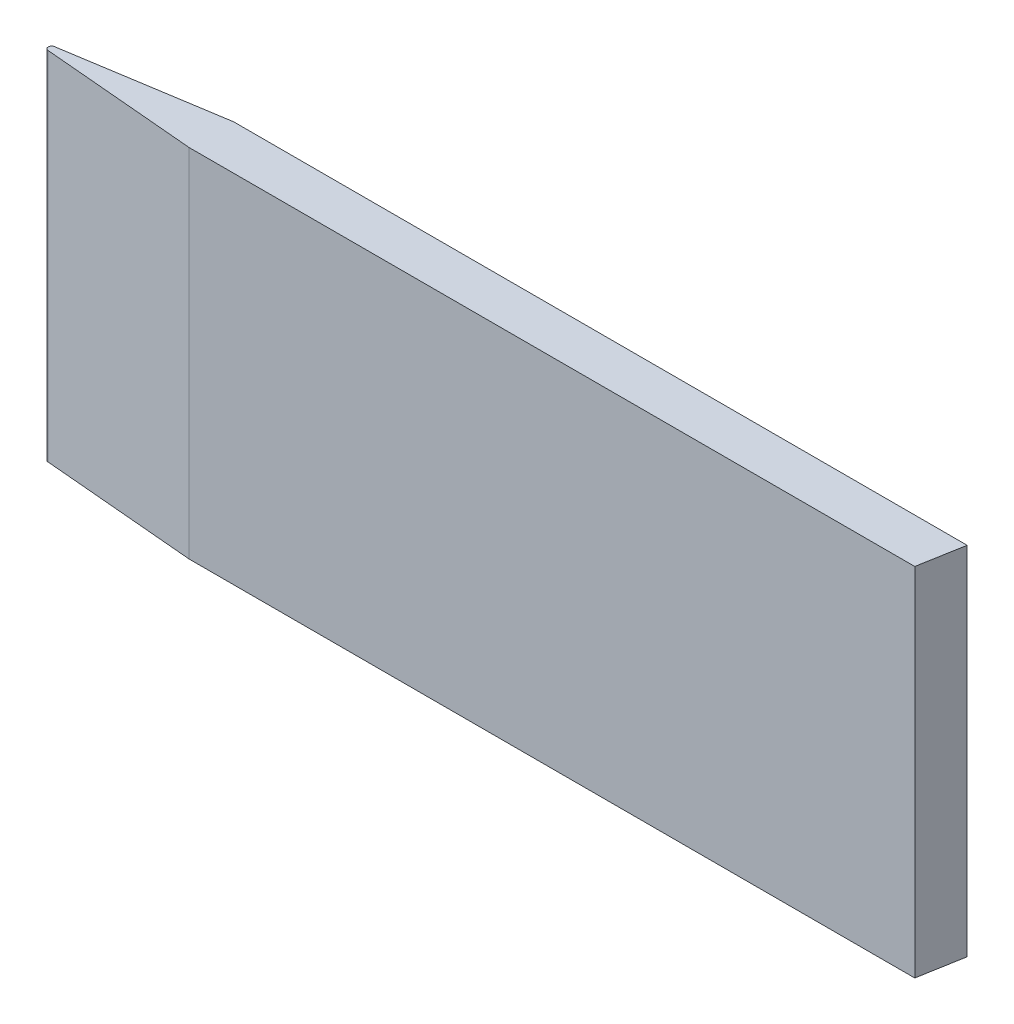
SolidWorks part; units mm, degrees
material "Acrylic (Medium-high impact)"
ref_plane "Front Plane" through (0, 0, 0) normal (0, 0, 1) x (1, 0, 0)
ref_plane "Top Plane" through (0, 0, 0) normal (0, 1, 0) x (1, 0, 0)
ref_plane "Right Plane" through (0, 0, 0) normal (1, 0, 0) x (0, 0, -1)
sketch "Sketch1" plane through (0, 0, 0) normal (0, 1, 0) x (1, 0, 0)
  line L0 (100, 5) -> (98.2367, -5)
  line L1 (-64.6456, -5) -> (98.2367, -5)
  line L2 (-100, -1.3113) -> (-100, -1.1547)
  line L3 (-64.6456, 5) -> (100, 5)
  line L5 (-100, -5) -> (100, 5) construction
  line L6 (-100, 5) -> (100, -5) construction
  line L7 (-99.4517, -0.5127) -> (-64.6456, 5)
  line L8 (-99.4067, -1.9588) -> (-64.6456, -5)
  arc A0 (-99.4067, -1.9588) -> (-100, -1.3113) centre (-99.35, -1.3113) cw
  arc A1 (-99.4517, -0.5127) -> (-100, -1.1547) centre (-99.35, -1.1547) ccw
  point P0 (0, 0)
  dimension "D6" = 0.65
  dimension "D1" = 10
  dimension "D2" = 200
  dimension "D3" = 80
  dimension "D4" = 99
  dimension "D5" = 95
extrude "Boss-Extrude1" add sketch "Sketch1" along normal blind 80
